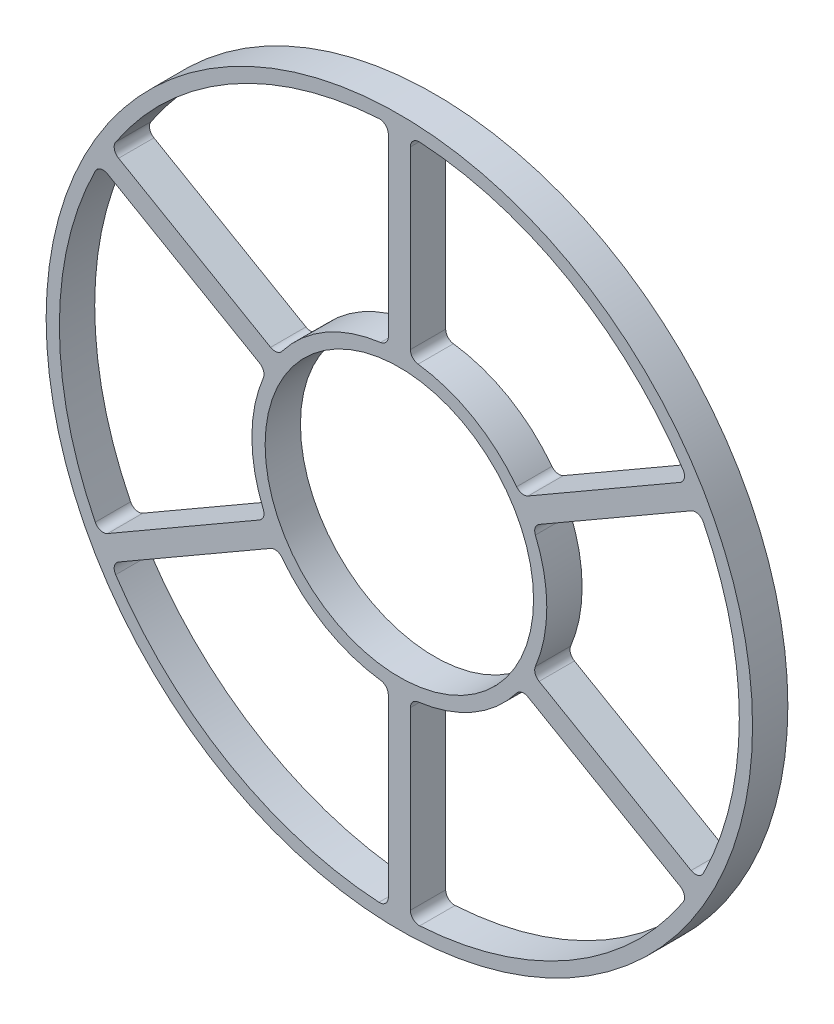
SolidWorks part; units mm, degrees
ref_plane "Front Plane" through (0, 0, 0) normal (0, 0, 1) x (1, 0, 0)
ref_plane "Top Plane" through (0, 0, 0) normal (0, 1, 0) x (1, 0, 0)
ref_plane "Right Plane" through (0, 0, 0) normal (1, 0, 0) x (0, 0, -1)
sketch "Sketch1" plane through (0, 0, 0) normal (0, 0, 1) x (1, 0, 0)
  line L0 (-1.25, 16.6532) -> (-1.25, 38.4797)
  line L1 (1.25, 38.4797) -> (1.25, 16.6532)
  line L2 (33.9494, 18.1573) -> (15.0471, 7.244)
  line L3 (13.7971, 9.4091) -> (32.6994, 20.3224)
  line L4 (32.6994, -20.3224) -> (13.7971, -9.4091)
  line L5 (15.0471, -7.244) -> (33.9494, -18.1573)
  line L6 (-1.25, -38.4797) -> (-1.25, -16.6532)
  line L7 (1.25, -16.6532) -> (1.25, -38.4797)
  line L8 (-33.9494, -18.1573) -> (-15.0471, -7.244)
  line L9 (-13.7971, -9.4091) -> (-32.6994, -20.3224)
  line L10 (-32.6994, 20.3224) -> (-13.7971, 9.4091)
  line L11 (-15.0471, 7.244) -> (-33.9494, 18.1573)
  circle A0 centre (0, 0) radius 15.2
  arc A1 (-13.7971, -9.4091) -> (-1.25, -16.6532) centre (0, 0) ccw
  arc A2 (-33.9494, 18.1573) -> (-33.9494, -18.1573) centre (0, 0) ccw
  circle A4 centre (0, 0) radius 40
  circle A5 centre (0, 0) radius 38.5 construction
  arc A6 (-32.6994, -20.3224) -> (-1.25, -38.4797) centre (0, 0) ccw
  arc A7 (-15.0471, 7.244) -> (-15.0471, -7.244) centre (0, 0) ccw
  arc A8 (-1.25, 16.6532) -> (-13.7971, 9.4091) centre (0, 0) ccw
  arc A9 (-1.25, 38.4797) -> (-32.6994, 20.3224) centre (0, 0) ccw
  arc A10 (32.6994, 20.3224) -> (1.25, 38.4797) centre (0, 0) ccw
  arc A11 (13.7971, 9.4091) -> (1.25, 16.6532) centre (0, 0) ccw
  arc A12 (15.0471, -7.244) -> (15.0471, 7.244) centre (0, 0) ccw
  arc A13 (33.9494, -18.1573) -> (33.9494, 18.1573) centre (0, 0) ccw
  arc A14 (1.25, -16.6532) -> (13.7971, -9.4091) centre (0, 0) ccw
  arc A15 (1.25, -38.4797) -> (32.6994, -20.3224) centre (0, 0) ccw
  point P3 (0, 0)
  point P11 (0, 0)
  point P12 (20.6739, 18.8836)
  point P13 (0, 0)
  point P34 (0, 0)
  point P35 (0, 0)
  dimension "D1" = 30.4
  dimension "D2" = 1.5
  dimension "D3" = 1.5
  dimension "D4" = 80
  dimension "D5" = 2.5
  dimension "D6" = 6
extrude "Boss-Extrude1" add sketch "Sketch1" along normal mid plane 4 contours A4 A15 L7 A14 L4 A13 L5 A12 L2 A9 L0 A8 L10 A6 L9 A1 L6 A0 L11 A7 L8 A2 L3 A11 L1 A10
fillet "Fillet2" radius 1 24 edges at (-15.0471, -7.244, 0) (32.6994, 20.3224, 0) (1.25, 38.4797, 0) (1.25, 16.6532, 0) (13.7971, 9.4091, 0) (-33.9494, 18.1573, 0) (-33.9494, -18.1573, 0) (-15.0471, 7.244, 0) (-1.25, -38.4797, 0) (-1.25, -16.6532, 0) (-13.7971, -9.4091, 0) (-32.6994, -20.3224, 0) (-32.6994, 20.3224, 0) (-13.7971, 9.4091, 0) (-1.25, 16.6532, 0) (-1.25, 38.4797, 0) (33.9494, 18.1573, 0) (15.0471, 7.244, 0) (15.0471, -7.244, 0) (33.9494, -18.1573, 0) (32.6994, -20.3224, 0) (13.7971, -9.4091, 0) (1.25, -16.6532, 0) (1.25, -38.4797, 0)
